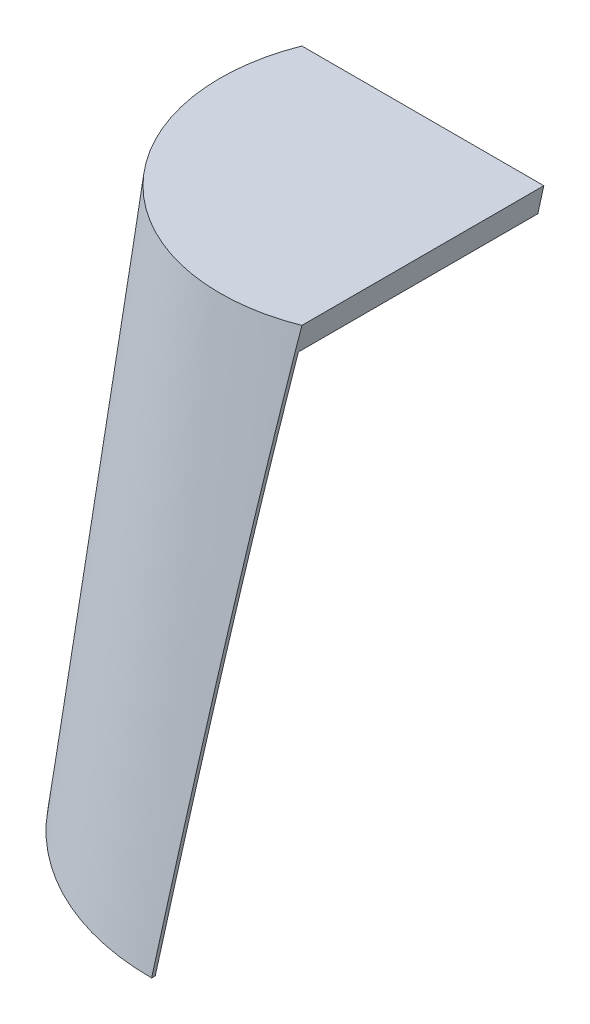
SolidWorks part; units mm, degrees
ref_plane "Front Plane" through (0, 0, 0) normal (0, 0, 1) x (1, 0, 0)
ref_plane "Top Plane" through (0, 0, 0) normal (0, 1, 0) x (1, 0, 0)
ref_plane "Right Plane" through (0, 0, 0) normal (1, 0, 0) x (0, 0, -1)
sketch "Sketch2" plane through (0, 0, 0) normal (0, 1, 0) x (1, 0, 0)
  circle A0 centre (0, 0) radius 105
  dimension "D1" = 210
extrude "Boss-Extrude1" add sketch "Sketch2" along normal blind 230 draft 7
sketch "Sketch3" plane through (0, 0, 0) normal (0, -1, 0) x (1, 0, 0)
  circle A0 centre (0, 0) radius 103.5
  dimension "D1" = 207
extrude "Cut-Extrude1" cut sketch "Sketch3" against normal blind 220 draft 7
sketch "Sketch4" plane through (0, 0, 0) normal (0, -1, 0) x (1, 0, 0)
  line L0 (-105, 0) -> (0, 0)
  line L1 (0, 0) -> (0, 105)
  arc A0 (0, 105) -> (-105, 0) centre (0, 0) cw
  circle A1 centre (0, 0) radius 105 construction
extrude "Cut-Extrude2" cut sketch "Sketch4" against normal up to surface (230 mm away) draft 7
